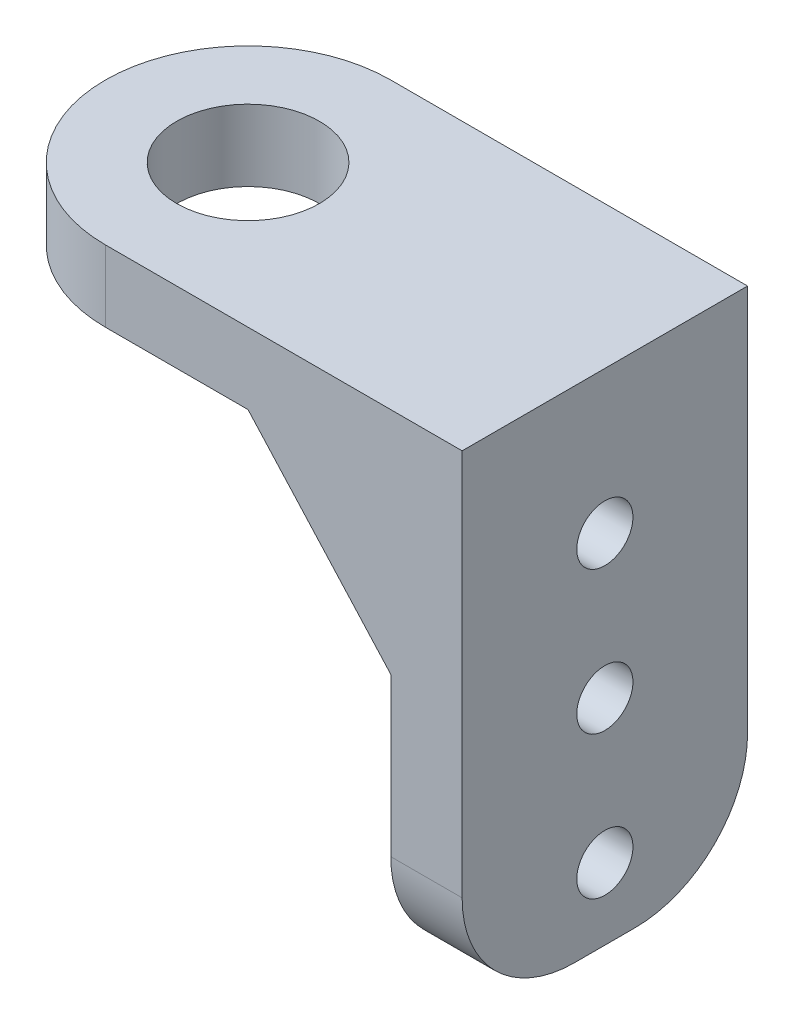
SolidWorks part; units mm, degrees
ref_plane "Front Plane" through (0, 0, 0) normal (0, 0, 1) x (1, 0, 0)
ref_plane "Top Plane" through (0, 0, 0) normal (0, 1, 0) x (1, 0, 0)
ref_plane "Right Plane" through (0, 0, 0) normal (1, 0, 0) x (0, 0, -1)
sketch "Sketch1" plane through (0, 0, 0) normal (0, 1, 0) x (1, 0, 0)
  line L0 (0, 12.7) -> (31.75, 12.7)
  line L1 (31.75, 12.7) -> (31.75, -12.7)
  line L2 (31.75, -12.7) -> (0, -12.7)
  line L3 (12.7, 0) -> (12.7, 12.7) construction
  circle A0 centre (0, 0) radius 6.35
  circle A1 centre (0, 0) radius 12.7
  dimension "D1" = 12.7
  dimension "D3" = 19.05
  dimension "D2" = 6.35
extrude "Boss-Extrude1" add sketch "Sketch1" along normal mid plane 6.35 contours A1 A0 | L3 A1 L2 L1 L0 | A1 L3 L0
sketch "Sketch2" plane through (0, 0, 12.7) normal (0, 0, 1) x (1, 0, 0)
  line L1 (31.75, -3.175) -> (25.4, -3.175)
  line L2 (31.75, -3.175) -> (31.75, -41.275)
  line L3 (31.75, -41.275) -> (25.4, -41.275)
  line L4 (25.4, -3.175) -> (25.4, -41.275)
  dimension "D1" = 6.35
  dimension "D2" = 38.1
extrude "Boss-Extrude2" add sketch "Sketch2" against normal up to surface (25.4 mm away) up to face at (15.875, 0, -12.7)
sketch "Sketch3" plane through (25.4, 0, 0) normal (-1, 0, 0) x (0, 0, 1)
  line L0 (0, -3.175) -> (0, -41.275) construction
  line L1 (-12.7, -3.175) -> (12.7, -3.175) construction
  line L2 (-12.7, -41.275) -> (12.7, -41.275) construction
  circle A0 centre (0, -34.925) radius 2.5
  circle A1 centre (0, -9.525) radius 2.5
  circle A2 centre (0, -22.225) radius 2.5
  point P12 (0, -22.225)
  dimension "D1" = 25.4
  dimension "D3" = 5
  dimension "D2" = 6.35
extrude "Cut-Extrude1" cut sketch "Sketch3" against normal through all
fillet "Fillet1" radius 10 2 edges at (28.575, -41.275, -12.7) (28.575, -41.275, 12.7)
ref_plane "Plane1" through (0, 0, 8.7) normal (0, 0, 1) x (1, 0, 0)
sketch "Sketch4" plane through (0, 0, 8.7) normal (0, 0, 1) x (1, 0, 0)
  line L0 (12.7, -3.175) -> (25.4, -17.225)
  line L1 (25.4, -3.175) -> (0, -3.175) construction
  line L2 (25.4, -3.175) -> (25.4, -31.275) construction
rib "Rib13" sketch "Sketch4" sketch "Sketch4" thickness 4 parameters "D1"=4
mirror "Mirror1" about plane through (0, 0, 0) normal (0, 0, 1) of "Rib13"
